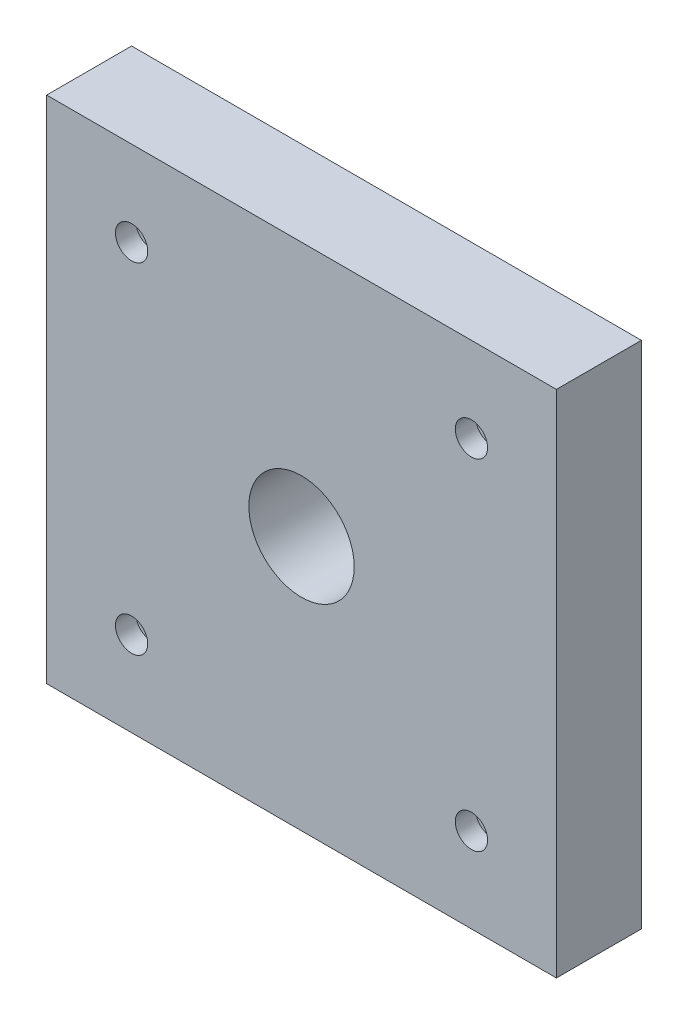
SolidWorks part; units mm, degrees
ref_plane "Front Plane" through (0, 0, 0) normal (0, 0, 1) x (1, 0, 0)
ref_plane "Top Plane" through (0, 0, 0) normal (0, 1, 0) x (1, 0, 0)
ref_plane "Right Plane" through (0, 0, 0) normal (1, 0, 0) x (0, 0, -1)
sketch "Sketch2" plane through (0, 0, 0) normal (0, 0, 1) x (1, 0, 0)
  line L1 (-38.1, -38.1) -> (38.1, -38.1)
  line L2 (-38.1, -38.1) -> (-38.1, 38.1)
  line L3 (-38.1, 38.1) -> (38.1, 38.1)
  line L4 (38.1, -38.1) -> (38.1, 38.1)
  line L5 (-38.1, -38.1) -> (38.1, 38.1) construction
  line L6 (-38.1, 38.1) -> (38.1, -38.1) construction
  circle A0 centre (0, 0) radius 7.874
  point P0 (0, 0)
  dimension "D3" = 15.748
  dimension "D1" = 76.2
  dimension "D2" = 76.2
extrude "Boss-Extrude1" add sketch "Sketch2" along normal blind 12.7
sketch "Sketch6" plane through (0, 0, 12.7) normal (0, 0, 1) x (1, 0, 0)
  line L0 (38.1, 38.1) -> (-38.1, 38.1) construction
  line L1 (-38.1, 38.1) -> (-38.1, -38.1) construction
  circle A0 centre (-25.4, 25.4) radius 2.413
  circle A1 centre (25.4, 25.4) radius 2.413
  circle A2 centre (25.4, -25.4) radius 2.413
  circle A3 centre (-25.4, -25.4) radius 2.413
  point P15 (0, 0)
  dimension "D1" = 4.826
  dimension "D2" = 12.7
  dimension "D3" = 12.7
  dimension "D4" = 4
extrude "Cut-Extrude3" cut sketch "Sketch6" against normal blind 3.048
sketch "Sketch7" plane through (0, 0, 9.652) normal (0, 0, 1) x (1, 0, 0)
  circle A0 centre (-25.4, 25.4) radius 1.524
  circle A1 centre (25.4, 25.4) radius 1.524
  circle A2 centre (25.4, -25.4) radius 1.524
  circle A3 centre (-25.4, -25.4) radius 1.524
  point P12 (0, 0)
  dimension "D1" = 3.048
  dimension "D2" = 4
extrude "Cut-Extrude4" cut sketch "Sketch7" against normal through all
